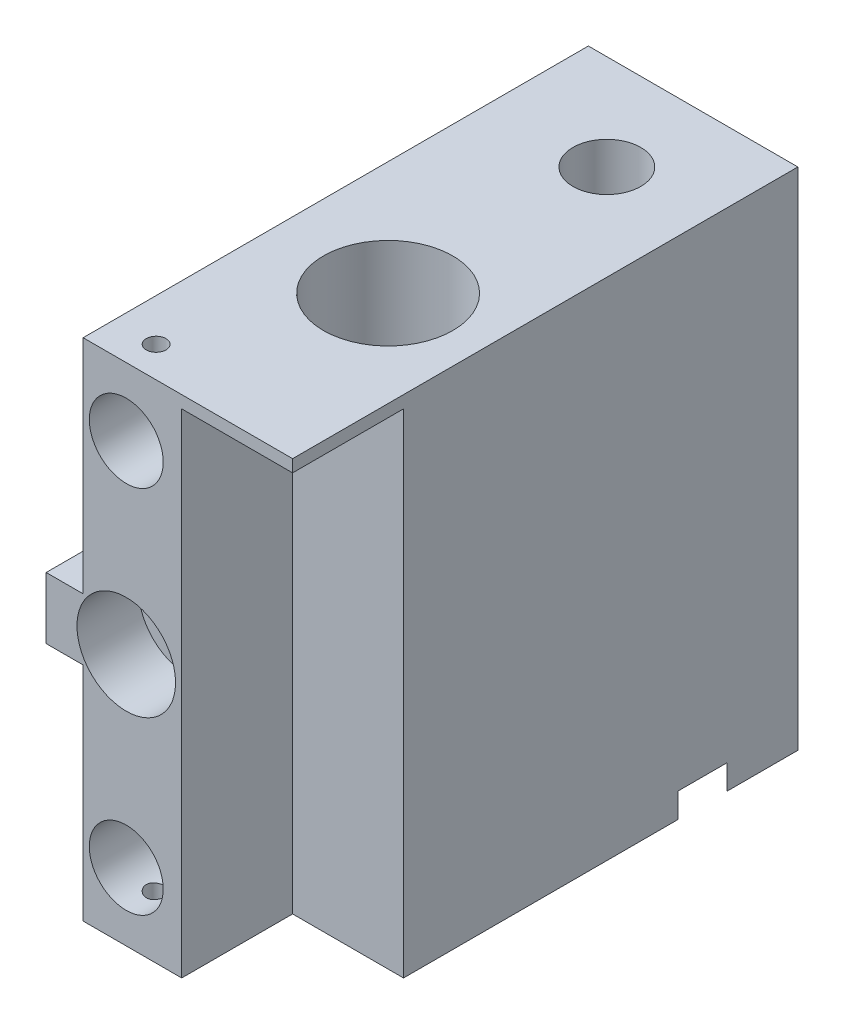
SolidWorks part; units mm, degrees
material "1060 Alloy"
ref_plane "Front Plane" through (0, 0, 0) normal (0, 0, 1) x (1, 0, 0)
ref_plane "Top Plane" through (0, 0, 0) normal (0, 1, 0) x (1, 0, 0)
ref_plane "Right Plane" through (0, 0, 0) normal (1, 0, 0) x (0, 0, -1)
sketch "Sketch1" plane through (0, 0, 0) normal (0, 0, 1) x (1, 0, 0)
  line L0 (-27, -17) -> (-27, -65) construction
  line L1 (0, 0) -> (-40, 0)
  line L2 (0, 0) -> (0, -82)
  line L3 (0, -82) -> (-40, -82)
  line L4 (-40, 0) -> (-40, -82)
  circle A0 centre (-27, -41) radius 5.5
  circle A1 centre (-27, -11) radius 6
  circle A2 centre (-27, -71) radius 6
  dimension "D3" = 11
  dimension "D4" = 12
  dimension "D5" = 12
  dimension "D1" = 40
  dimension "D2" = 82
  dimension "D6" = 11
  dimension "D7" = 30
  dimension "D8" = 13
  dimension "D9" = 30
  dimension "D10" = 11
extrude "Boss-Extrude1" add sketch "Sketch1" along normal blind 12
sketch "Sketch2" plane through (0, 0, 0) normal (0, 0, -1) x (-1, 0, 0)
  line L0 (0, -82) -> (0, 0) construction
  line L1 (40, -82) -> (0, -82) construction
  line L2 (40, 0) -> (40, -82) construction
  line L3 (0, 0) -> (40, 0) construction
  line L4 (0, -82) -> (0, 0)
  line L5 (40, -82) -> (0, -82)
  line L6 (40, 0) -> (40, -82)
  line L7 (0, 0) -> (40, 0)
  circle A0 centre (27, -41) radius 5.5 construction
  circle A1 centre (27, -41) radius 5.5
extrude "Boss-Extrude2" add sketch "Sketch2" along normal blind 70
sketch "Sketch3" plane through (0, 0, 0) normal (0, 1, 0) x (1, 0, 0)
  line L0 (-40, -5) -> (0, -5) construction
  line L1 (-40, -12) -> (-40, 70) construction
  line L2 (0, -12) -> (0, 70) construction
  line L3 (0, -12) -> (-40, -12) construction
  circle A0 centre (-27.1548, -7) radius 1.6
  dimension "D1" = 3.2
  dimension "D2" = 5
  dimension "D3" = 13
extrude "Cut-Extrude1" cut sketch "Sketch3" against normal blind 10
sketch "Sketch4" plane through (0, -82, 0) normal (0, -1, 0) x (1, 0, 0)
  circle A1 centre (-27.1548, 7) radius 1.6
  circle A2 centre (-27.1548, 7) radius 1.6
  dimension "D1" = 0
extrude "Cut-Extrude2" cut sketch "Sketch4" against normal blind 10
sketch "Sketch5" plane through (0, 0, 0) normal (0, 1, 0) x (1, 0, 0)
  line L0 (-15.5, 70) -> (-15.5, 49) construction
  line L1 (-40, 70) -> (0, 70) construction
  line L2 (0, -12) -> (-40, -12) construction
  line L3 (0, -12) -> (0, 70) construction
  line L4 (-15.5, 60) -> (-15.5, 49) construction
  line L5 (-15.5, 29.5) -> (-15.5, 8.5) construction
  line L6 (-15.5, 29.5) -> (-15.5, -12) construction
  circle A1 centre (-15.5, 19) radius 10.5
  circle A2 centre (-15.5, 54.5) radius 5.5
  dimension "D2" = 11
  dimension "D3" = 25
  dimension "D4" = 21
  dimension "D1" = 15.5
  dimension "D6" = 51
extrude "Cut-Extrude3" cut sketch "Sketch5" against normal blind 100
sketch "Sketch6" plane through (0, -82, 0) normal (0, 1, 0) x (1, 0, 0)
  circle A0 centre (-15.5, 54.5) radius 16
  dimension "D1" = 32
extrude "Cut-Extrude4" cut sketch "Sketch6" along normal blind 4
sketch "Sketch19" plane through (0, -78, 0) normal (0, -1, 0) x (-1, 0, 0)
  circle A0 centre (15.5, 54.5) radius 8.05
  dimension "D1" = 16.1
extrude "Cut-Extrude17" cut sketch "Sketch19" against normal blind 16
sketch "Sketch12" plane through (0, -78, 0) normal (0, -1, 0) x (-1, 0, 0)
  line L1 (26.8198, 50.5172) -> (30.8026, 61.837) construction
  line L2 (30.8026, 61.837) -> (19.4828, 65.8198) construction
  line L3 (4.1802, 58.4828) -> (0.1974, 47.163) construction
  line L4 (0.1974, 47.163) -> (11.5172, 43.1802) construction
  circle A0 centre (15.5, 54.5) radius 12 construction
  circle A1 centre (11.5172, 43.1802) radius 1.2
  circle A2 centre (26.8198, 50.5172) radius 1.2
  circle A3 centre (19.4828, 65.8198) radius 1.2
  circle A4 centre (4.1802, 58.4828) radius 1.2
  dimension "D1" = 24
  dimension "D2" = 2.4
extrude "Cut-Extrude12" cut sketch "Sketch12" against normal blind 12
sketch "Sketch13" plane through (0, 0, -70) normal (0, 0, -1) x (-1, 0, 0)
  line L1 (40, 0) -> (60, 0)
  line L2 (40, 0) -> (40, -70)
  line L3 (40, -70) -> (60, -70)
  line L4 (60, 0) -> (60, -70)
  dimension "D1" = 20
  dimension "D2" = 70
extrude "Boss-Extrude3" add sketch "Sketch13" against normal blind 30
sketch "Sketch14" plane through (0, 0, -70) normal (0, 0, -1) x (-1, 0, 0)
  line L1 (50.54, -17.46) -> (27, -17.46) construction
  line L2 (3.46, -41) -> (3.46, -64.54) construction
  line L3 (3.46, -64.54) -> (27, -64.54) construction
  line L4 (50.54, -41) -> (50.54, -17.46) construction
  circle A0 centre (27, -41) radius 23.54 construction
  circle A1 centre (50.54, -41) radius 2
  circle A2 centre (27, -17.46) radius 2
  circle A3 centre (3.46, -41) radius 2
  circle A4 centre (27, -64.54) radius 2
  dimension "D1" = 47.08
  dimension "D2" = 4
extrude "Cut-Extrude13" cut sketch "Sketch14" against normal blind 12
sketch "Sketch15" plane through (0, 0, -70) normal (0, 0, -1) x (-1, 0, 0)
  line L0 (34, 0) -> (34, -36)
  line L1 (60, 0) -> (0, 0) construction
  line L2 (34, -36) -> (54.5811, -36)
  line L4 (34, -82) -> (34, -46)
  line L5 (0, -82) -> (11.5314, -82) construction
  line L6 (34, -46) -> (54.5811, -46)
  line L7 (54.5811, -46) -> (54.5811, -36)
  line L8 (34, 0) -> (77.5206, 0)
  line L9 (77.5206, 0) -> (77.5206, -82)
  line L10 (77.5206, -82) -> (34, -82)
  line L11 (60, -70) -> (60, 0) construction
  dimension "D1" = 26
  dimension "D2" = 10
  dimension "D3" = 36
  dimension "D4" = 36
extrude "Cut-Extrude14" cut sketch "Sketch15" against normal blind 115
sketch "Sketch18" plane through (0, 0, -70) normal (0, 0, -1) x (-1, 0, 0)
  circle A0 centre (27, -41) radius 19.1
  dimension "D1" = 38.2
extrude "Cut-Extrude16" cut sketch "Sketch18" against normal blind 2
sketch "Sketch22" plane through (0, -82, 0) normal (0, -1, 0) x (1, 0, 0)
  line L1 (0, 12) -> (-18, 12)
  line L2 (0, 12) -> (0, -6)
  line L3 (0, -6) -> (-18, -6)
  line L4 (-18, 12) -> (-18, -6)
  dimension "D1" = 18
  dimension "D2" = 18
extrude "Cut-Extrude18" cut sketch "Sketch22" against normal blind 80
sketch "Sketch23" plane through (0, 0, 12) normal (0, 0, 1) x (1, 0, 0)
  circle A0 centre (-27, -41) radius 8
  dimension "D1" = 16
extrude "Cut-Extrude19" cut sketch "Sketch23" against normal blind 10
